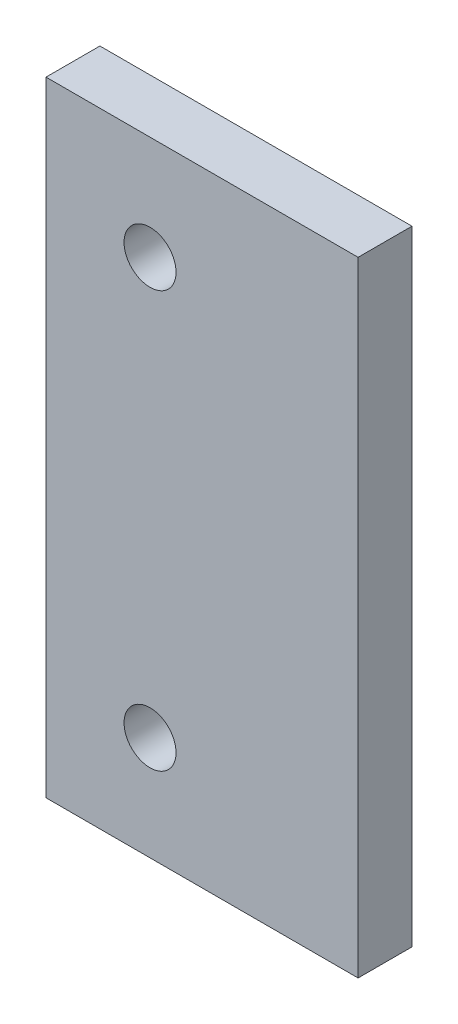
SolidWorks part; units mm, degrees
material "6061 Alloy"
ref_plane "X-Y Datum" through (0, 0, 0) normal (0, 0, 1) x (1, 0, 0)
ref_plane "X-Z Datum" through (0, 0, 0) normal (0, 1, 0) x (1, 0, 0)
ref_plane "Y-Z Datum" through (0, 0, 0) normal (1, 0, 0) x (0, 0, -1)
sketch "Sketch1" plane through (0, 0, 0) normal (0, 0, 1) x (1, 0, 0)
  line L1 (-19.05, -38.1) -> (19.05, -38.1)
  line L2 (-19.05, -38.1) -> (-19.05, 38.1)
  line L3 (-19.05, 38.1) -> (19.05, 38.1)
  line L4 (19.05, -38.1) -> (19.05, 38.1)
  line L5 (-19.05, -38.1) -> (19.05, 38.1) construction
  line L6 (-19.05, 38.1) -> (19.05, -38.1) construction
  point P0 (0, 0)
  dimension "D1" = 38.1
  dimension "D2" = 76.2
extrude "Boss-Extrude1" add sketch "Sketch1" along normal blind 6.5786
sketch "Sketch2" plane through (0, 0, 6.5786) normal (0, 0, 1) x (1, 0, 0)
  line L0 (-19.05, 38.1) -> (-19.05, -38.1) construction
  line L1 (-19.05, -38.1) -> (19.05, -38.1) construction
  line L2 (19.05, 38.1) -> (-19.05, 38.1) construction
  point P0 (-6.35, 25.4)
  point P1 (-6.35, -25.4)
  dimension "D1" = 12.7
  dimension "D2" = 12.7
  dimension "D3" = 12.7
  dimension "D4" = 12.7
hole_wizard "#97 (0.25) Diameter Hole1" positions "3DSketch1" profile "Sketch3" hole size "#97" standard "ANSI Inch" end condition through all
sketch3d "3DSketch1"
  point P0 (-6.35, 25.4, 6.5786)
  point P3 (-6.35, -25.4, 6.5786)
sketch "Sketch3" plane through (-6.35, 25.4, 6.5786) normal (1, 0, 0) x (0, -1, 0)
  line L0 (0, 0) -> (0, 6.5786)
  line L1 (0, 6.5786) -> (3.175, 6.5786)
  line L2 (3.175, 6.5786) -> (3.175, 0)
  line L5 (3.175, 0) -> (0, 0)
  line L11 (0, -6.35) -> (0, 107.95) construction
  dimension "Thru Hole Dia." = 6.35
  dimension "Thru Hole Depth" = 6.5786
